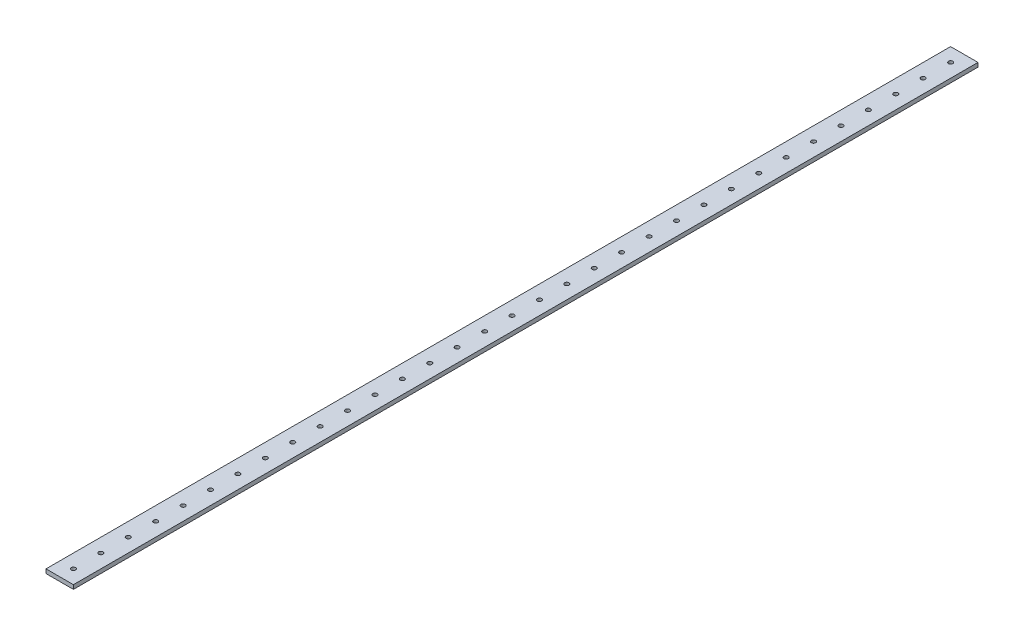
SolidWorks part; units mm, degrees
ref_plane "前视基准面" through (0, 0, 0) normal (0, 0, 1) x (1, 0, 0)
ref_plane "上视基准面" through (0, 0, 0) normal (0, 1, 0) x (1, 0, 0)
ref_plane "右视基准面" through (0, 0, 0) normal (1, 0, 0) x (0, 0, -1)
other "Configuration Table"
sketch "草图1" plane through (0, 0, 0) normal (0, 0, 1) x (1, 0, 0)
  line L1 (0, 0) -> (20, 0)
  line L2 (0, 0) -> (0, -3)
  line L3 (0, -3) -> (20, -3)
  line L4 (20, 0) -> (20, -3)
  dimension "D1" = 20
  dimension "D2" = 3
extrude "凸台-拉伸1" add sketch "草图1" along normal blind 660
sketch "草图2" plane through (0, 0, 0) normal (0, 1, 0) x (1, 0, 0)
  line L1 (20, 0) -> (0, 0) construction
  line L2 (10, 0) -> (10, -10) construction
  circle A0 centre (10, -10) radius 1.575
  circle A1 centre (10, -30) radius 1.575
  circle A2 centre (10, -50) radius 1.575
  circle A3 centre (10, -70) radius 1.575
  circle A4 centre (10, -90) radius 1.575
  circle A5 centre (10, -110) radius 1.575
  circle A6 centre (10, -130) radius 1.575
  circle A7 centre (10, -150) radius 1.575
  circle A8 centre (10, -170) radius 1.575
  circle A9 centre (10, -190) radius 1.575
  circle A10 centre (10, -210) radius 1.575
  circle A11 centre (10, -230) radius 1.575
  circle A12 centre (10, -250) radius 1.575
  circle A13 centre (10, -270) radius 1.575
  circle A14 centre (10, -290) radius 1.575
  circle A15 centre (10, -310) radius 1.575
  circle A16 centre (10, -330) radius 1.575
  circle A17 centre (10, -350) radius 1.575
  circle A18 centre (10, -370) radius 1.575
  circle A19 centre (10, -390) radius 1.575
  circle A20 centre (10, -410) radius 1.575
  circle A21 centre (10, -430) radius 1.575
  circle A22 centre (10, -450) radius 1.575
  circle A23 centre (10, -470) radius 1.575
  circle A24 centre (10, -490) radius 1.575
  circle A25 centre (10, -510) radius 1.575
  circle A26 centre (10, -530) radius 1.575
  circle A27 centre (10, -550) radius 1.575
  circle A28 centre (10, -570) radius 1.575
  circle A29 centre (10, -590) radius 1.575
  circle A30 centre (10, -610) radius 1.575
  circle A31 centre (10, -630) radius 1.575
  circle A32 centre (10, -650) radius 1.575
  dimension "D1" = 3.15
  dimension "D2" = 33
  dimension "D3" = 10
  dimension "D4" = 20
extrude "切除-拉伸1" cut sketch "草图2" against normal through all
